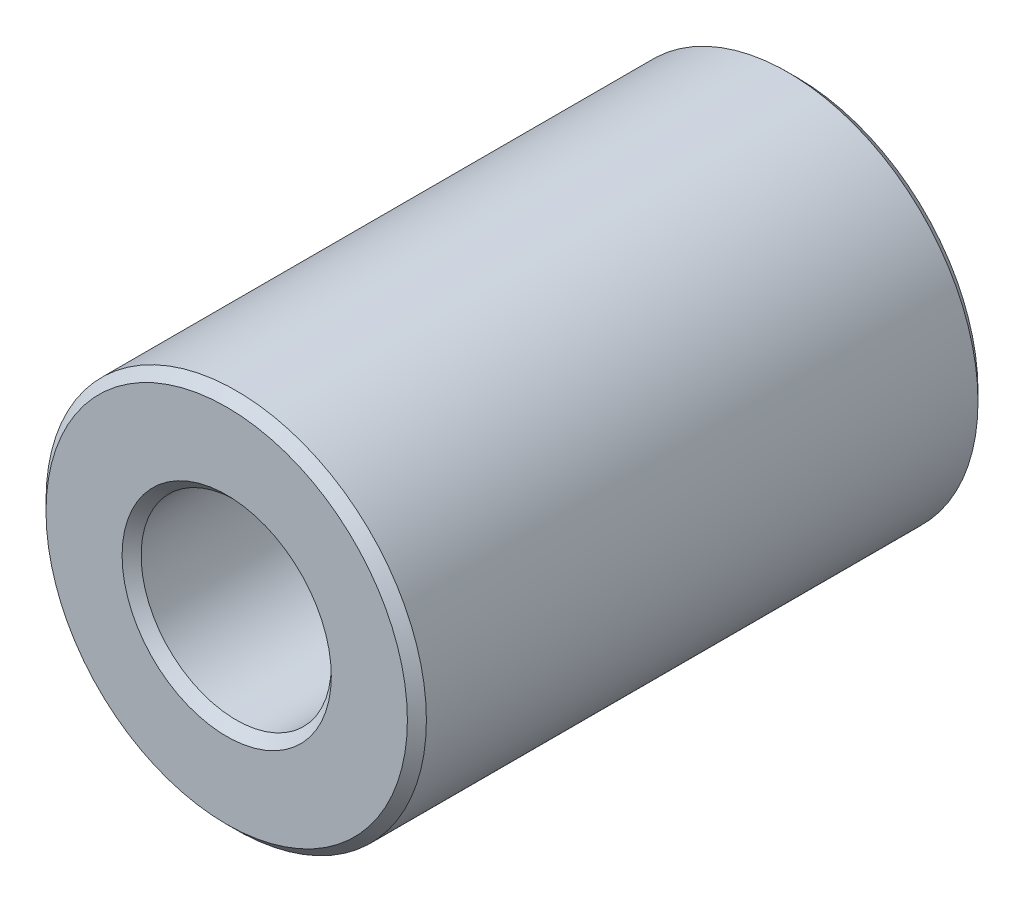
SolidWorks part; units mm, degrees
ref_plane "前视基准面" through (0, 0, 0) normal (0, 0, 1) x (1, 0, 0)
ref_plane "上视基准面" through (0, 0, 0) normal (0, 1, 0) x (1, 0, 0)
ref_plane "右视基准面" through (0, 0, 0) normal (1, 0, 0) x (0, 0, -1)
sketch "草图2" plane through (0, 0, 0) normal (0, 0, 1) x (1, 0, 0)
  circle A0 centre (0, 0) radius 2
  circle A1 centre (0, 0) radius 4
  dimension "D1" = 4
  dimension "D2" = 8
extrude "凸台-拉伸1" add sketch "草图2" along normal mid plane 12
chamfer "倒角1" distance 0.2 angle 45 4 edges at (2, 0, 6) (2, 0, -6) (4, 0, -6) (4, 0, 6)
